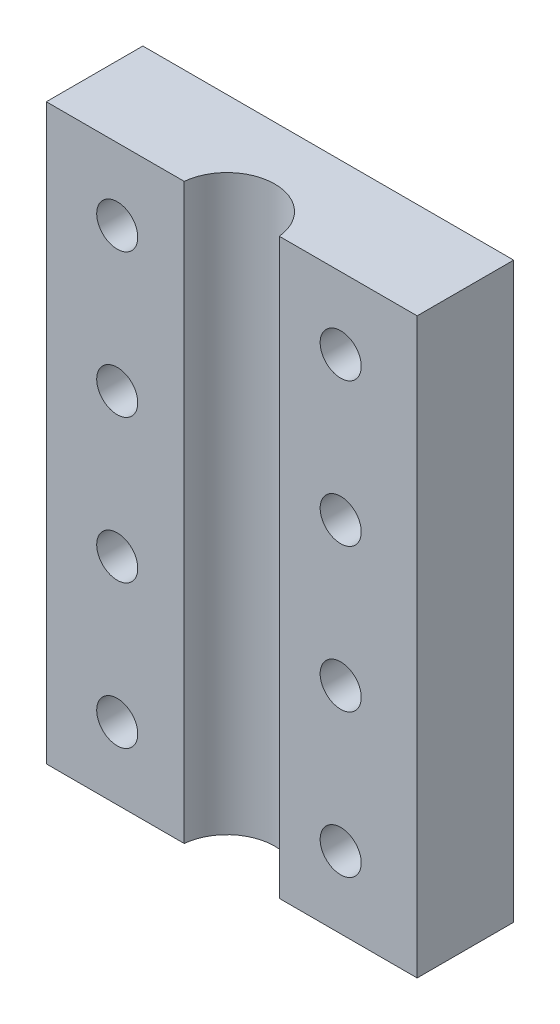
SolidWorks part; units mm, degrees
ref_plane "前视基准面" through (0, 0, 0) normal (0, 0, 1) x (1, 0, 0)
ref_plane "上视基准面" through (0, 0, 0) normal (0, 1, 0) x (1, 0, 0)
ref_plane "右视基准面" through (0, 0, 0) normal (1, 0, 0) x (0, 0, -1)
other "Configuration Table"
sketch "草图1" plane through (0, 0, 0) normal (0, 1, 0) x (1, 0, 0)
  line L5 (-19.4, 10.1) -> (19.4, 10.1)
  line L6 (-19.4, 10.1) -> (-19.4, 0)
  line L7 (-19.4, 0) -> (19.4, 0)
  line L8 (19.4, 10.1) -> (19.4, 0)
  point P4 (0, 0)
  dimension "D1" = 10.1
  dimension "D2" = 38.8
extrude "凸台-拉伸1" add sketch "草图1" along normal blind 60
sketch "草图2" plane through (0, 60, 0) normal (0, 1, 0) x (1, 0, 0)
  line L0 (-19.4, 0) -> (19.4, 0) construction
  circle A0 centre (0, -0.5) radius 5
  dimension "D1" = 10
  dimension "D2" = 0.5
extrude "切除-拉伸1" cut sketch "草图2" against normal blind 60
sketch "草图3" plane through (0, 0, -10.1) normal (0, 0, -1) x (-1, 0, 0)
  line L0 (-19.4, 60) -> (19.4, 60) construction
  line L1 (-19.4, 60) -> (-19.4, 0) construction
  circle A0 centre (-11.4, 52.5) radius 2.15
  circle A1 centre (-11.4, 37.5) radius 2.15
  circle A2 centre (-11.4, 22.5) radius 2.15
  circle A3 centre (-11.4, 7.5) radius 2.15
  circle A4 centre (11.98, 52.5) radius 2.15
  circle A5 centre (11.98, 37.5) radius 2.15
  circle A6 centre (11.98, 22.5) radius 2.15
  circle A7 centre (11.98, 7.5) radius 2.15
  dimension "D4" = 4.3
  dimension "D1" = 7.5
  dimension "D2" = 8
  dimension "D3" = 4
  dimension "D5" = 2
extrude "切除-拉伸2" cut sketch "草图3" against normal through all
